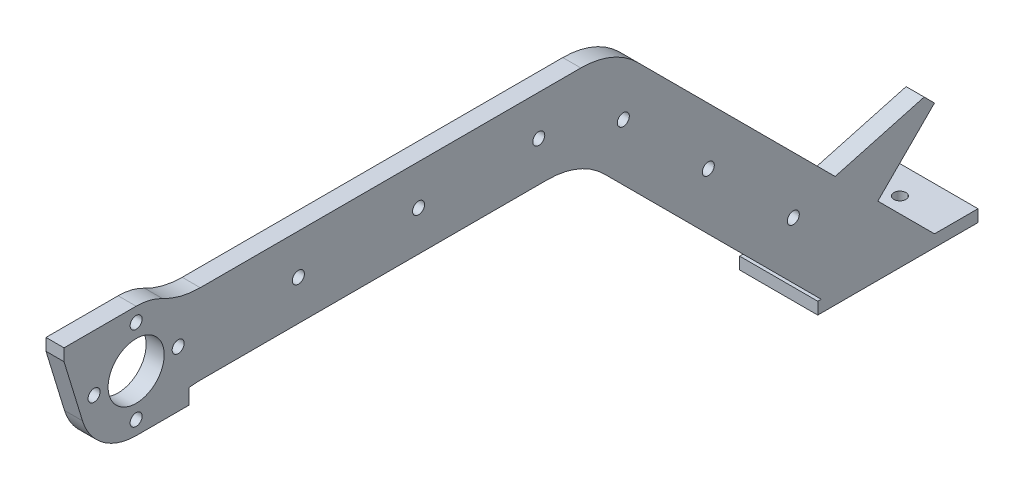
SolidWorks part; units mm, degrees
ref_plane "前视基准面" through (0, 0, 0) normal (0, 0, 1) x (1, 0, 0)
ref_plane "上视基准面" through (0, 0, 0) normal (0, 1, 0) x (1, 0, 0)
ref_plane "右视基准面" through (0, 0, 0) normal (1, 0, 0) x (0, 0, -1)
sketch "草图1" plane through (0, 0, 0) normal (1, 0, 0) x (0, 0, -1)
  line L2 (116.8579, -15.8579) -> (171, -70)
  line L3 (171, -70) -> (199.2843, -70)
  line L4 (199.2843, -70) -> (125.1421, 4.1421)
  line L5 (111, 10) -> (16, 10)
  line L7 (16, -10) -> (102.7369, -10)
  line L8 (186.193, -71.0509) -> (123.8062, -8.664) construction
  line L9 (0, 14) -> (-18, 14)
  line L10 (-18, 14) -> (-18, 11)
  line L11 (-18, 11) -> (-13.3889, -4.091)
  line L12 (13.2242, -14) -> (13.2242, -10)
  line L13 (0, -14) -> (13.2242, -14)
  arc A0 (6.5882, 12.3529) -> (6.5882, -12.3529) centre (0, 0) ccw
  circle A1 centre (0, 0) radius 10.5 construction
  circle A2 centre (0, 0) radius 7
  circle A3 centre (0, 10.5) radius 1.5
  circle A4 centre (10.5, 0) radius 1.5
  circle A5 centre (0, -10.5) radius 1.5
  circle A6 centre (-10.5, 0) radius 1.5
  arc A7 (125.1421, 4.1421) -> (111, 10) centre (111, -10) ccw
  arc A8 (102.7369, -10) -> (116.8579, -15.8579) centre (102.7157, -30) cw
  circle A9 centre (40.5, 0) radius 1.5
  circle A10 centre (70.5, 0) radius 1.5
  circle A11 centre (100.5, 0) radius 1.5
  circle A12 centre (121.61, -6.4679) radius 1.5
  circle A13 centre (142.8232, -27.6811) radius 1.5
  circle A14 centre (164.0364, -48.8943) radius 1.5
  arc A15 (16, 10) -> (6.5882, 12.3529) centre (16, 30) cw
  arc A16 (16, -10) -> (6.5882, -12.3529) centre (16, -30) ccw
  point P36 (185.1421, -70)
  point P43 (9.798, 7.7889)
  point P50 (9.798, -10)
  dimension "D1" = 28
  dimension "D2" = 21
  dimension "D3" = 14
  dimension "D4" = 3
  dimension "D9" = 20
  dimension "D13" = 3
  dimension "D16" = 30
  dimension "D17" = 3
  dimension "D19" = 30
  dimension "D24" = 20
  dimension "D25" = 20
  dimension "D6" = 135
  dimension "D7" = 20
  dimension "D8" = 171
  dimension "D10" = 70
  dimension "D11" = 20
  dimension "D14" = 40.5
  dimension "D18" = 21.11
  dimension "D20" = 30
  dimension "D21" = 18
  dimension "D22" = 3
  dimension "D26" = 13.2242
  dimension "D28" = 20
  dimension "D15" = 3
  dimension "D5" = 4
extrude "凸台-拉伸1" add sketch "草图1" along normal mid plane 4.5
sketch "草图3" plane through (0, -70, 0) normal (0, -1, 0) x (1, 0, 0)
  line L0 (2.25, -116.8579) -> (2.25, -171) construction
  line L1 (2.25, -170.1443) -> (-17.25, -170.1443)
  line L2 (2.25, -170.1443) -> (2.25, -210.1443)
  line L3 (2.25, -210.1443) -> (-17.25, -210.1443)
  line L4 (-17.25, -170.1443) -> (-17.25, -210.1443)
  dimension "D1" = 19.5
  dimension "D2" = 40
  dimension "D3" = 10.86
extrude "凸台-拉伸2" add sketch "草图3" along normal blind 3
sketch "草图4" plane through (0, -70, 0) normal (0, 1, 0) x (1, 0, 0)
  line L0 (-17.25, 190.1443) -> (2.25, 190.1443) construction
  line L1 (-17.25, 170.1443) -> (-17.25, 210.1443) construction
  line L2 (2.25, 199.2843) -> (2.25, 125.1421) construction
  line L3 (-17.25, 210.1443) -> (2.25, 210.1443) construction
  circle A0 centre (-10.25, 203.1443) radius 1.5
  circle A1 centre (-10.25, 177.1443) radius 1.5
  dimension "D1" = 3
  dimension "D2" = 7
  dimension "D3" = 7
extrude "切除-拉伸1" cut sketch "草图4" against normal through all
sketch "草图5" plane through (0, 64.6421, -64.6421) normal (0, 0.7071, -0.7071) x (1, 0, 0)
  line L0 (-2.25, 170.4127) -> (-2.25, 190.4127) construction
  line L1 (-2.25, 170.4127) -> (2.25, 170.4127)
  line L2 (-2.25, 170.4127) -> (-2.25, 155.3402)
  line L3 (-2.25, 155.3402) -> (2.25, 155.3402)
  line L4 (2.25, 170.4127) -> (2.25, 155.3402)
  line L5 (-2.25, 190.4127) -> (-2.25, 85.5599) construction
  line L6 (2.25, 190.4127) -> (2.25, 85.5599) construction
extrude "凸台-拉伸3" add sketch "草图5" along normal blind 20
sketch "草图6" plane through (-2.25, 0, 0) normal (-1, 0, 0) x (0, 0, 1)
  line L0 (-196.4277, -38.8592) -> (-174.4842, -45.2)
  line L1 (-199.2843, -41.7157) -> (-188.6264, -31.0578) construction
sketch "草图7" plane through (-2.25, 0, 0) normal (-1, 0, 0) x (0, 0, 1)
  line L0 (-197.0619, -39.4934) -> (-174.4842, -45.2)
  line L1 (-199.2843, -41.7157) -> (-188.6264, -31.0578) construction
sketch "草图9" plane through (-2.25, 0, 0) normal (-1, 0, 0) x (0, 0, 1)
  line L0 (-196.6995, -39.131) -> (-174.4842, -45.2)
  line L1 (-199.2843, -41.7157) -> (-188.6264, -31.0578) construction
  line L16 (-13.2242, -10.1936) -> (-13.2242, -14)
  line L17 (-13.2242, -14) -> (0, -14)
  line L18 (13.3889, -4.091) -> (18, 11)
  line L19 (18, 11) -> (18, 14)
  line L20 (18, 14) -> (0, 14)
  line L21 (-16, 10) -> (-111, 10)
  line L22 (-125.1421, 4.1421) -> (-174.4842, -45.2)
  line L23 (-174.4842, -45.2) -> (-188.6264, -31.0578)
  line L24 (-188.6264, -31.0578) -> (-199.2843, -41.7157)
  line L25 (-199.2843, -41.7157) -> (-185.1421, -55.8579)
  line L26 (-185.1421, -55.8579) -> (-199.2843, -70)
  line L27 (-199.2843, -70) -> (-171, -70)
  line L28 (-171, -70) -> (-116.8579, -15.8579)
  line L29 (-102.7369, -10) -> (-16, -10)
  line L37 (-174.4842, -45.2) -> (-188.6264, -31.0578)
  line L38 (-188.6264, -31.0578) -> (-196.6995, -39.131)
  arc A6 (-13.2242, -10.1936) -> (-16, -10) centre (-16, -30) ccw
  arc A7 (0, -14) -> (13.3889, -4.091) centre (0, 0) ccw
  arc A8 (0, 14) -> (-6.5882, 12.3529) centre (0, 0) ccw
  arc A9 (-16, 10) -> (-6.5882, 12.3529) centre (-16, 30) ccw
  arc A10 (-111, 10) -> (-125.1421, 4.1421) centre (-111, -10) ccw
  arc A11 (-102.7369, -10) -> (-116.8579, -15.8579) centre (-102.7157, -30) ccw
  dimension "D1" = 0
extrude "切除-拉伸3" cut sketch "草图9" against normal blind 10
